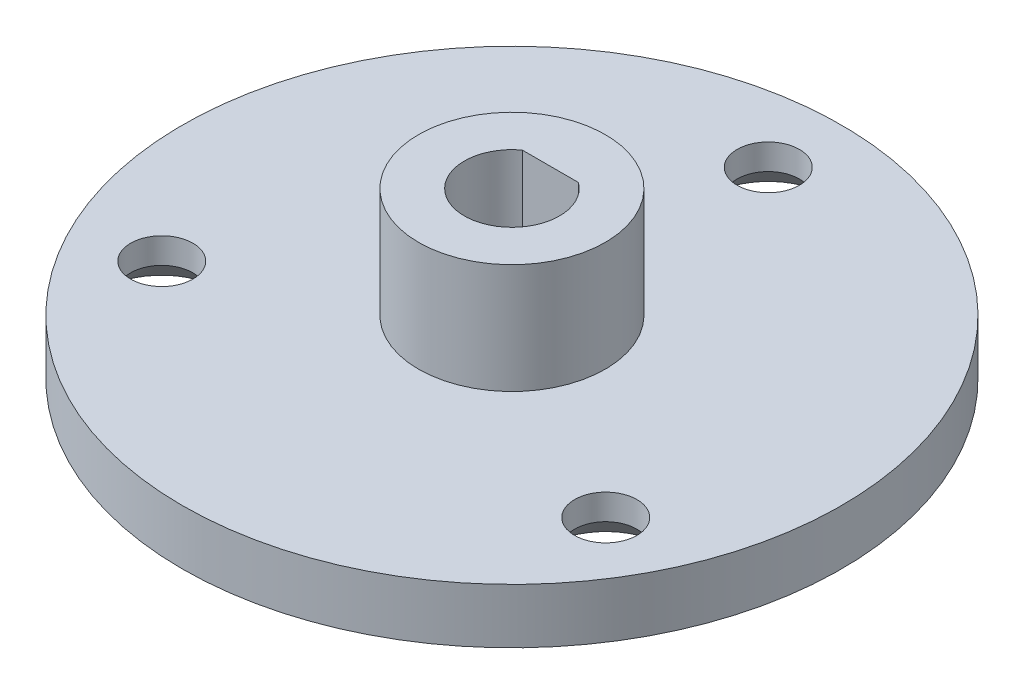
SolidWorks part; units mm, degrees
ref_plane "前视基准面" through (0, 0, 0) normal (0, 0, 1) x (1, 0, 0)
ref_plane "上视基准面" through (0, 0, 0) normal (0, 1, 0) x (1, 0, 0)
ref_plane "右视基准面" through (0, 0, 0) normal (1, 0, 0) x (0, 0, -1)
other "Configuration Table"
sketch "草图1" plane through (0, 0, 0) normal (0, 1, 0) x (1, 0, 0)
  line L0 (-12.1244, -7) -> (12.1244, -7) construction
  line L1 (-12.1244, -7) -> (0, 14) construction
  line L2 (0, 14) -> (12.1244, -7) construction
  line L3 (-1.533, 2.1) -> (1.533, 2.1)
  circle A0 centre (0, 0) radius 18
  circle A1 centre (0, 0) radius 14 construction
  circle A2 centre (-12.1244, -7) radius 1.6
  circle A3 centre (0, 14) radius 1.6
  circle A4 centre (12.1244, -7) radius 1.6
  circle A5 centre (0, 0) radius 2.6
  point P6 (0, 14)
  point P16 (0, 0)
  point P17 (0, 0)
  point P18 (0, 0)
  dimension "D1" = 36
  dimension "D2" = 28
  dimension "D4" = 3.2
  dimension "D6" = 5.2
  dimension "D3" = 60
  dimension "D7" = 2.1
  dimension "D5" = 3
extrude "凸台-拉伸1" add sketch "草图1" along normal blind 3 contours A0 A5 A4 A3 A2 | L3 A5
hole_wizard "打孔尺寸(%根据十字)槽沉头木螺钉的类型2" positions "草图7" profile "草图8" countersink size "M3" standard "GB" end condition through all
sketch "草图7" plane through (0, 0, 0) normal (0, -1, 0) x (-1, 0, 0)
  point P0 (-12.1244, -7)
  point P3 (12.1244, -7)
  point P6 (0, 14)
sketch "草图8" plane through (12.1244, 0, 7) normal (1, 0, 0) x (0, 0, -1)
  line L0 (0, 0) -> (0, 3)
  line L1 (0, 3) -> (1.7, 3)
  line L2 (1.7, 3) -> (1.7, 1.6)
  line L3 (1.7, 1.6) -> (3.3, 0)
  line L5 (3.3, 0) -> (0, 0)
  line L6 (-1.7, 1.6) -> (-3.3, 0) construction
  line L11 (0, -6.35) -> (0, 107.95) construction
  dimension "通孔孔直径" = 3.4
  dimension "通孔孔深度" = 3
  dimension "近端锥形沉头孔直径" = 6.6
  dimension "近端锥形沉头孔角度" = 90
sketch "草图9" plane through (0, 3, 0) normal (0, 1, 0) x (1, 0, 0)
  line L0 (-1.533, 2.1) -> (1.533, 2.1) construction
  line L1 (-1.533, 2.1) -> (1.533, 2.1)
  circle A0 centre (0, 0) radius 5.1
  arc A1 (-1.533, 2.1) -> (1.533, 2.1) centre (0, 0) ccw construction
  arc A2 (-1.533, 2.1) -> (1.533, 2.1) centre (0, 0) ccw
  dimension "D1" = 2.5
extrude "凸台-拉伸2" add sketch "草图9" along normal blind 6
